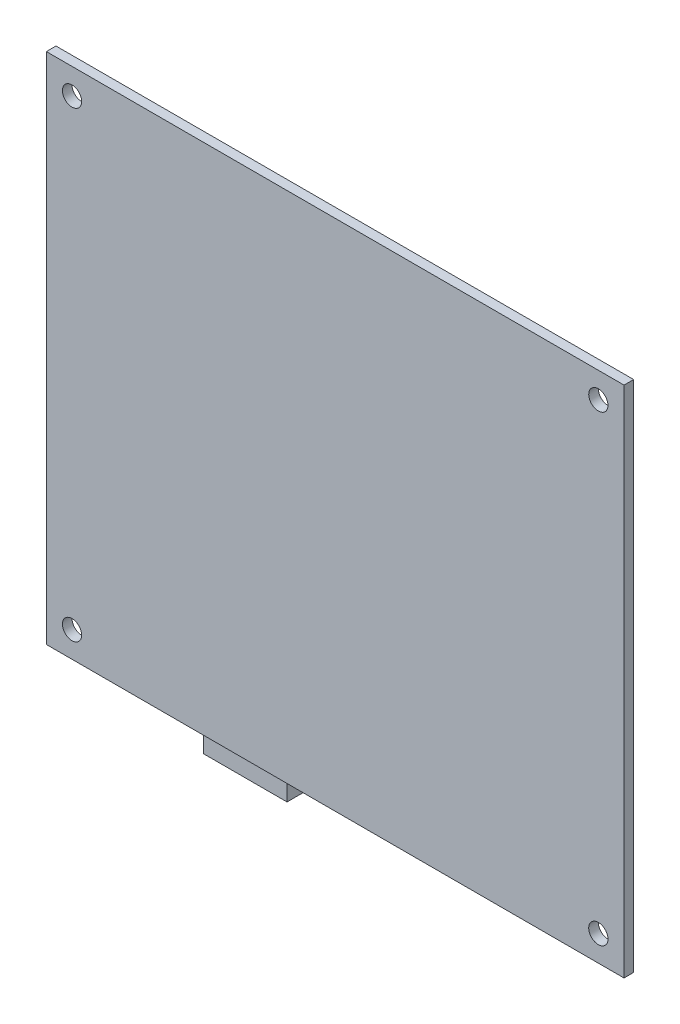
SolidWorks part; units mm, degrees
ref_plane "前视基准面" through (0, 0, 0) normal (0, 0, 1) x (1, 0, 0)
ref_plane "上视基准面" through (0, 0, 0) normal (0, 1, 0) x (1, 0, 0)
ref_plane "右视基准面" through (0, 0, 0) normal (1, 0, 0) x (0, 0, -1)
other "Configuration Table"
sketch "草图1" plane through (0, 0, 0) normal (0, 0, 1) x (1, 0, 0)
  line L0 (45, 80) -> (45, 66.0789) construction
  line L1 (0, 0) -> (90, 0)
  line L2 (0, 0) -> (0, 80)
  line L3 (0, 80) -> (90, 80)
  line L4 (90, 0) -> (90, 80)
  line L5 (0, 40) -> (11.5683, 40) construction
  circle A0 centre (4, 76) radius 1.5
  circle A1 centre (86, 76) radius 1.5
  circle A2 centre (86, 4) radius 1.5
  circle A3 centre (4, 4) radius 1.5
  point P17 (0, 0)
  dimension "D5" = 3
  dimension "D1" = 90
  dimension "D2" = 80
  dimension "D3" = 82
  dimension "D4" = 72
extrude "凸台-拉伸1" add sketch "草图1" along normal blind 1.5
sketch "草图2" plane through (0, 0, 0) normal (0, -1, 0) x (1, 0, 0)
  line L0 (0, 0) -> (90, 0) construction
  line L1 (23, 0) -> (36, 0)
  line L2 (23, 0) -> (23, -8)
  line L3 (23, -8) -> (36, -8)
  line L4 (36, 0) -> (36, -8)
  line L5 (0, 1.5) -> (0, 0) construction
  dimension "D1" = 23
  dimension "D2" = 8
  dimension "D3" = 13
extrude "凸台-拉伸2" add sketch "草图2" along normal blind 4 separate body
sketch "草图3" plane through (0, 0, 0) normal (0, 1, 0) x (1, 0, 0)
  line L0 (90, 0) -> (0, 0) construction
  line L1 (23, 8) -> (36, 8)
  line L2 (23, 8) -> (23, 0)
  line L3 (23, 0) -> (36, 0)
  line L4 (36, 8) -> (36, 0)
  line L5 (10, 0) -> (20, 0)
  line L6 (10, 0) -> (10, 12)
  line L7 (10, 12) -> (20, 12)
  line L8 (20, 0) -> (20, 12)
  dimension "D1" = 3
  dimension "D2" = 12
  dimension "D3" = 10
extrude "凸台-拉伸3" add sketch "草图3" along normal blind 15
sketch "草图4" plane through (0, -4, 0) normal (0, -1, 0) x (1, 0, 0)
  line L0 (25.1561, -1.2196) -> (23.8536, -2.5221)
  line L1 (23.8536, -2.5221) -> (23.8536, -5.5868)
  line L2 (23.8536, -5.5868) -> (25.0028, -6.7361)
  line L3 (25.0028, -6.7361) -> (35.1163, -6.7361)
  line L4 (35.1163, -6.7361) -> (35.1163, -1.2196)
  line L5 (35.1163, -1.2196) -> (25.1561, -1.2196)
  circle A0 centre (26.6118, -3.9779) radius 1.7622
  circle A1 centre (32.4347, -3.9779) radius 1.7218
  point P9 (35.1163, -6.7361)
extrude "切除-拉伸1" cut sketch "草图4" against normal blind 4
